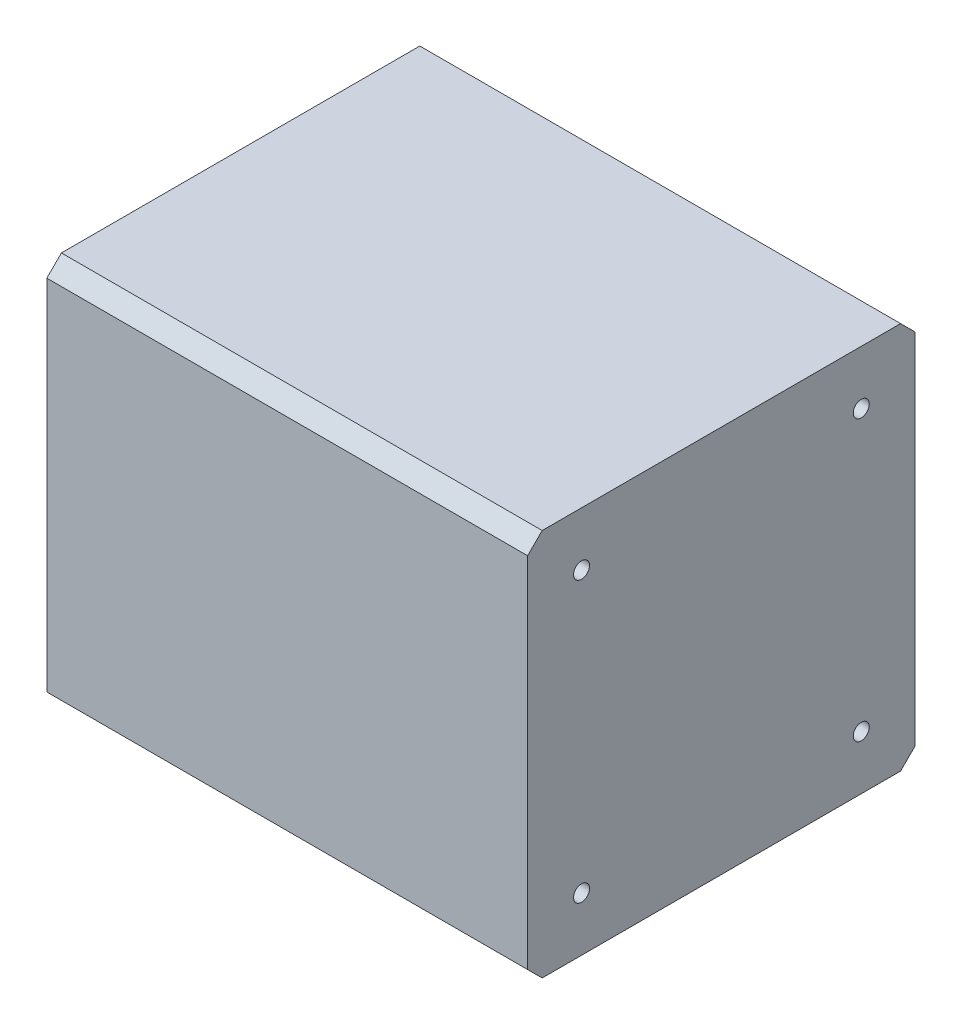
SolidWorks part; units mm, degrees
ref_plane "前视基准面" through (0, 0, 0) normal (0, 0, 1) x (1, 0, 0)
ref_plane "上视基准面" through (0, 0, 0) normal (0, 1, 0) x (1, 0, 0)
ref_plane "右视基准面" through (0, 0, 0) normal (1, 0, 0) x (0, 0, -1)
sketch "草图1" plane through (0, 0, 0) normal (1, 0, 0) x (0, 0, -1)
  line L1 (-66.5, 66.5) -> (66.5, 66.5)
  line L2 (-66.5, 66.5) -> (-66.5, -66.5)
  line L3 (-66.5, -66.5) -> (66.5, -66.5)
  line L4 (66.5, 66.5) -> (66.5, -66.5)
  line L5 (-61.25, 61.25) -> (61.25, 61.25)
  line L6 (-61.25, 61.25) -> (-61.25, -61.25)
  line L7 (-61.25, -61.25) -> (61.25, -61.25)
  line L8 (61.25, 61.25) -> (61.25, -61.25)
  dimension "D1" = 133
  dimension "D2" = 66.5
  dimension "D3" = 66.5
  dimension "D4" = 122.5
  dimension "D5" = 61.25
  dimension "D6" = 61.25
extrude "凸台-拉伸1" add sketch "草图1" along normal blind 160
sketch "草图2" plane through (160, 0, 0) normal (1, 0, 0) x (0, 0, -1)
  line L0 (66.5, 66.5) -> (-66.5, 66.5) construction
  line L1 (66.5, 66.5) -> (-66.5, 66.5)
  line L2 (66.5, -66.5) -> (66.5, 66.5) construction
  line L3 (-66.5, -66.5) -> (66.5, -66.5) construction
  line L4 (-66.5, 66.5) -> (-66.5, -66.5) construction
  line L5 (66.5, -66.5) -> (66.5, 66.5)
  line L6 (-66.5, -66.5) -> (66.5, -66.5)
  line L7 (-66.5, 66.5) -> (-66.5, -66.5)
extrude "凸台-拉伸2" add sketch "草图2" along normal blind 5
chamfer "倒角1" distance 5 angle 45 4 edges at (82.5, -66.5, -66.5) (82.5, -66.5, 66.5) (82.5, 66.5, -66.5) (82.5, 66.5, 66.5)
sketch "草图3" plane through (165, 0, 0) normal (1, 0, 0) x (0, 0, -1)
  line L1 (-48, 48) -> (48, 48) construction
  line L2 (-48, 48) -> (-48, -48) construction
  line L3 (-48, -48) -> (48, -48) construction
  line L4 (48, 48) -> (48, -48) construction
  circle A0 centre (48, 48) radius 2.75
  circle A1 centre (48, -48) radius 2.75
  circle A2 centre (-48, -48) radius 2.75
  circle A3 centre (-48, 48) radius 2.75
  dimension "D4" = 5.5
  dimension "D1" = 96
  dimension "D2" = 48
  dimension "D3" = 48
extrude "切除-拉伸1" cut sketch "草图3" against normal blind 5
sketch "草图4" plane through (0, -66.5, 0) normal (0, -1, 0) x (1, 0, 0)
  line L0 (0, 61.5) -> (0, -61.5) construction
  line L1 (40, 20) -> (0, 20)
  line L3 (40, -20) -> (0, -20)
  line L4 (0, 20) -> (0, -20)
  arc A0 (40, -20) -> (40, 20) centre (40, 0) ccw
  dimension "D1" = 40
  dimension "D2" = 40
extrude "切除-拉伸2" cut sketch "草图4" against normal blind 10
